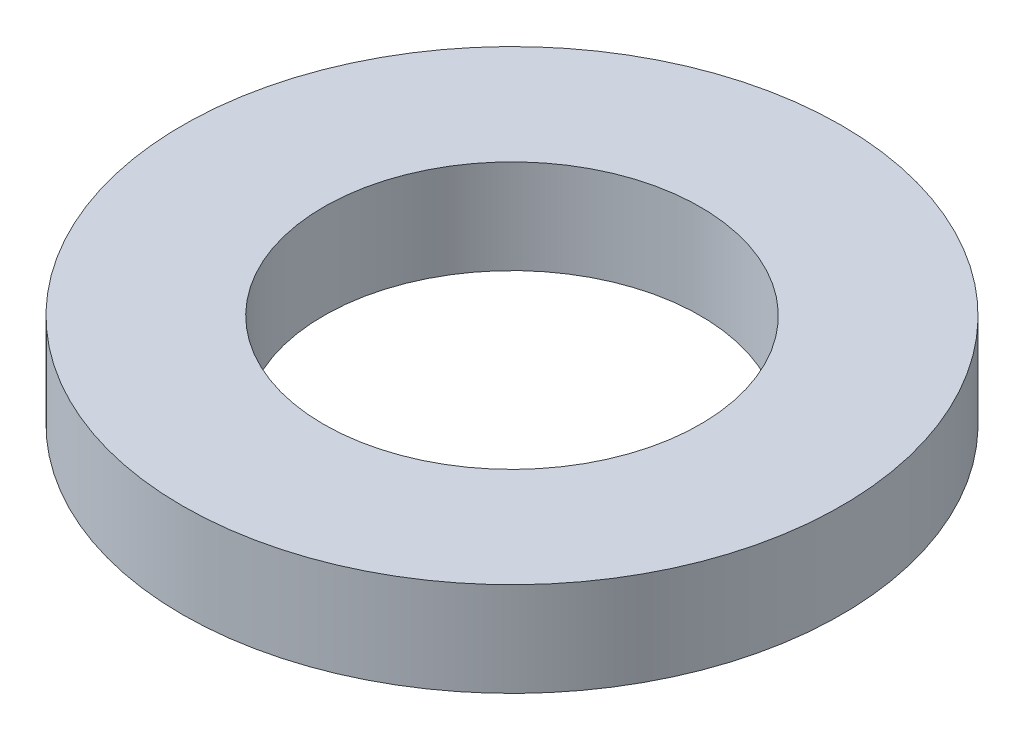
SolidWorks part; units mm, degrees
material "1023 Carbon Steel Sheet (SS)"
ref_plane "Front Plane" through (0, 0, 0) normal (0, 0, 1) x (1, 0, 0)
ref_plane "Top Plane" through (0, 0, 0) normal (0, 1, 0) x (1, 0, 0)
ref_plane "Right Plane" through (0, 0, 0) normal (1, 0, 0) x (0, 0, -1)
sketch "Sketch1" plane through (0, 0, 0) normal (0, 1, 0) x (1, 0, 0)
  circle A0 centre (0, 0) radius 2
  circle A1 centre (0, 0) radius 3.5
  dimension "D1" = 4
  dimension "D2" = 7
extrude "Boss-Extrude1" add sketch "Sketch1" along normal blind 1
